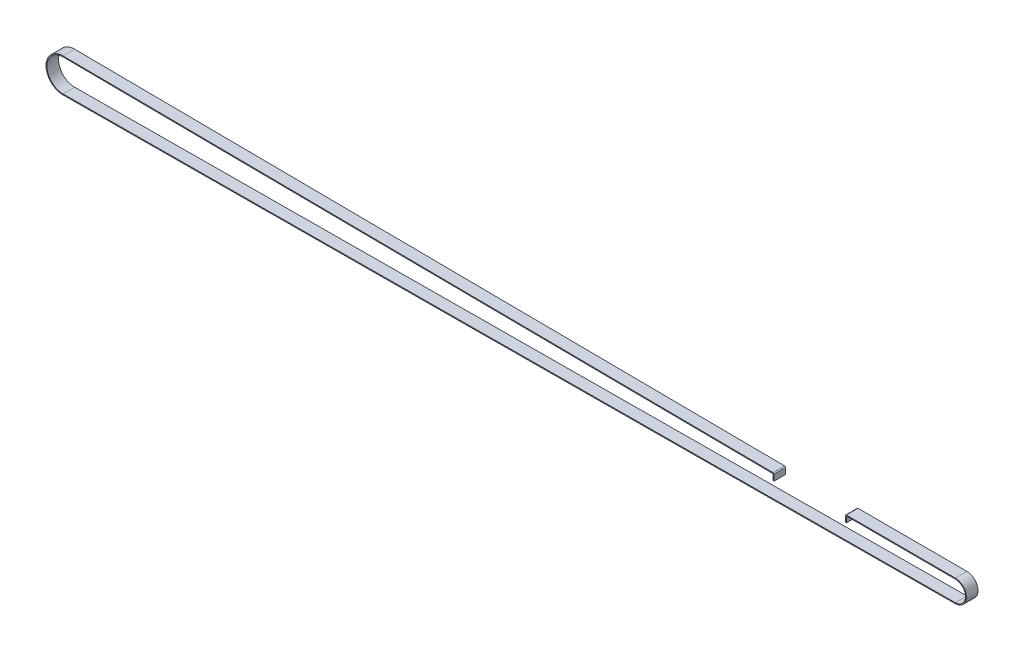
SolidWorks part; units mm, degrees
ref_plane "Front Plane" through (0, 0, 0) normal (0, 0, 1) x (1, 0, 0)
ref_plane "Top Plane" through (0, 0, 0) normal (0, 1, 0) x (1, 0, 0)
ref_plane "Right Plane" through (0, 0, 0) normal (1, 0, 0) x (0, 0, -1)
sketch "Sketch1" plane through (0, 0, 0) normal (0, 0, 1) x (1, 0, 0)
  line L0 (487.78, 5.4108) -> (0.0599, 8.7498) construction
  line L1 (0.0545, -8.7498) -> (487.7765, -5.7139) construction
  line L2 (487.78, 5.4108) -> (0.0599, 8.7498) construction
  line L3 (0.0545, -8.7498) -> (487.7765, -5.7139)
  line L4 (0.0599, 8.7498) -> (388.0665, 5.511)
  line L5 (386.1656, 5.411) -> (430.1656, 5.411) construction
  line L6 (388.1656, 5.411) -> (388.1656, 2.231)
  line L7 (386.1656, 2.231) -> (430.1656, 2.231) construction
  line L8 (388.1656, 2.231) -> (388.1656, 5.411) construction
  line L9 (428.1656, 2.231) -> (428.1656, 5.411)
  line L10 (428.2658, 5.511) -> (487.78, 5.4108)
  arc A0 (0.0599, 8.7498) -> (0.0545, -8.7498) centre (0, 0) ccw construction
  arc A1 (487.7765, -5.7139) -> (487.78, 5.4108) centre (487.7419, -0.1515) ccw construction
  arc A2 (0.0599, 8.7498) -> (0.0545, -8.7498) centre (0, 0) ccw
  arc A3 (487.7765, -5.7139) -> (487.78, 5.4108) centre (487.7419, -0.1515) ccw
  arc A4 (388.0665, 5.511) -> (388.1656, 5.411) centre (388.0656, 5.411) cw
  arc A5 (428.1656, 5.411) -> (428.2658, 5.511) centre (428.2656, 5.411) cw
  dimension "D1" = 0.1
  dimension "D2" = 0.1
extrude "Extrude-Thin1" add sketch "Sketch1" along normal blind 6.35 from offset 1 thin contours L2 A2 L3 A3
